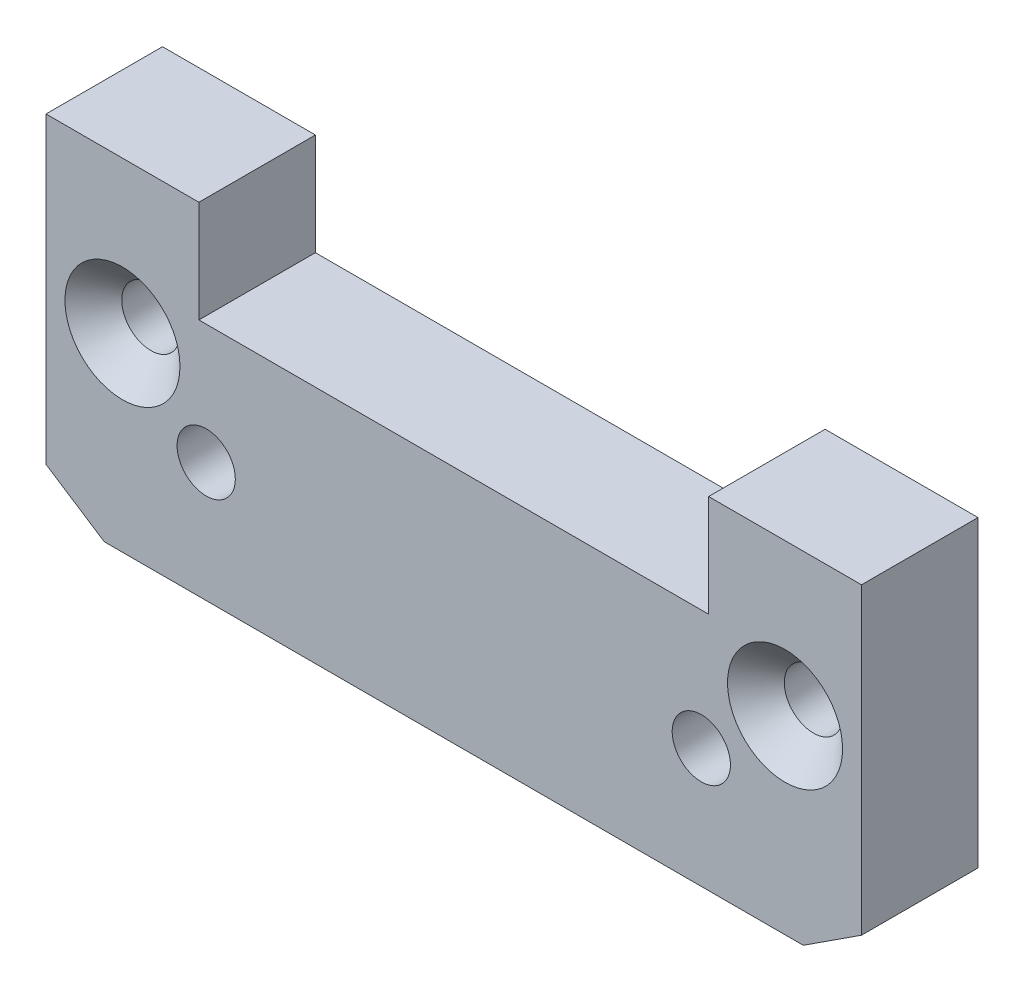
SolidWorks part; units mm, degrees
ref_plane "Front Plane" through (0, 0, 0) normal (0, 0, 1) x (1, 0, 0)
ref_plane "Top Plane" through (0, 0, 0) normal (0, 1, 0) x (1, 0, 0)
ref_plane "Right Plane" through (0, 0, 0) normal (1, 0, 0) x (0, 0, -1)
sketch "Sketch1" plane through (0, 0, 0) normal (0, 0, 1) x (1, 0, 0)
  line L0 (28, 0) -> (28, 10)
  line L1 (-28, 0) -> (-28, 10)
  line L12 (17.5, 10) -> (17.5, 3)
  line L13 (17.5, 3) -> (-17.5, 3)
  line L14 (-17.5, 3) -> (-17.5, 10)
  line L15 (-17.5, 10) -> (-56, 10)
  line L16 (-60, 6) -> (-60, 4)
  line L17 (-56, 0) -> (-28, 0)
  line L18 (-28, 0) -> (-28, -10.8424)
  line L19 (-24, -13.44) -> (24, -13.44)
  line L20 (28, -10.8424) -> (28, 0)
  line L21 (28, 0) -> (56, 0)
  line L22 (60, 4) -> (60, 6)
  line L23 (56, 10) -> (17.5, 10)
  line L24 (17.5, 10) -> (17.5, 3)
  line L25 (17.5, 3) -> (-17.5, 3)
  line L26 (-17.5, 3) -> (-17.5, 10)
  line L27 (-17.5, 10) -> (-28, 10)
  line L30 (-28, 0) -> (-28, -10.8424)
  line L31 (-24, -13.44) -> (24, -13.44)
  line L32 (28, -10.8424) -> (28, 0)
  line L35 (28, 10) -> (17.5, 10)
  line L1056 (24, -13.44) -> (28, -10.8424)
  line L1057 (24, -13.44) -> (28, -10.8424)
  line L1058 (-28, -10.8424) -> (-24, -13.44)
  line L1059 (-28, -10.8424) -> (-24, -13.44)
  arc A4 (-56, 10) -> (-60, 6) centre (-56, 6) ccw
  arc A5 (-60, 4) -> (-56, 0) centre (-56, 4) ccw
  arc A6 (56, 0) -> (60, 4) centre (56, 4) ccw
  arc A7 (60, 6) -> (56, 10) centre (56, 6) ccw
  dimension "D1" = 0
extrude "Boss-Extrude1" add sketch "Sketch1" along normal blind 8
hole_wizard "CSK for M4 SFHCS1" positions "Sketch2" profile "Sketch3" countersink size "M4" standard "ANSI Metric"
sketch "Sketch2" plane through (-695.683, 1385.2473, 13) normal (0, 0, 1) x (1, 0, 0)
  point P0 (678.683, -1390.4673)
  point P2 (712.683, -1390.4673)
sketch "Sketch3" plane through (-17, -5.22, 13) normal (1, 0, 0) x (0, -1, 0)
  line L0 (0, 0) -> (0, 14.2017)
  line L1 (0, 14.2017) -> (2, 13)
  line L2 (2, 13) -> (2, 1.95)
  line L3 (2, 1.95) -> (3.95, 0)
  line L4 (3.95, 0) -> (0, 0)
  line L5 (-2, 1.95) -> (-3.95, 0) construction
  line L6 (0, 14.2017) -> (-2, 13) construction
  line L7 (0, -6.35) -> (0, 107.95) construction
  dimension "Hole Dia." = 4
  dimension "Hole Depth" = 13
  dimension "Near C'Sink Dia." = 7.9
  dimension "Near C'Sink Angle" = 90
  dimension "Drill Angle" = 118
hole_wizard "CSK for M4 SFHCS2" positions "Sketch4" profile "Sketch5" countersink size "M4" standard "ANSI Metric"
sketch "Sketch4" plane through (-695.683, 1385.2473, 8) normal (0, 0, 1) x (1, 0, 0)
  point P0 (672.933, -1385.6685)
  point P2 (718.433, -1385.6685)
sketch "Sketch5" plane through (-22.75, -0.4212, 8) normal (1, 0, 0) x (0, -1, 0)
  line L0 (0, 0) -> (0, 17.2017)
  line L1 (0, 17.2017) -> (2, 16)
  line L2 (2, 16) -> (2, 1.95)
  line L3 (2, 1.95) -> (3.95, 0)
  line L4 (3.95, 0) -> (0, 0)
  line L5 (-2, 1.95) -> (-3.95, 0) construction
  line L6 (0, 17.2017) -> (-2, 16) construction
  line L7 (0, -6.35) -> (0, 107.95) construction
  dimension "Hole Dia." = 4
  dimension "Hole Depth" = 16
  dimension "Near C'Sink Dia." = 7.9
  dimension "Near C'Sink Angle" = 90
  dimension "Drill Angle" = 118
